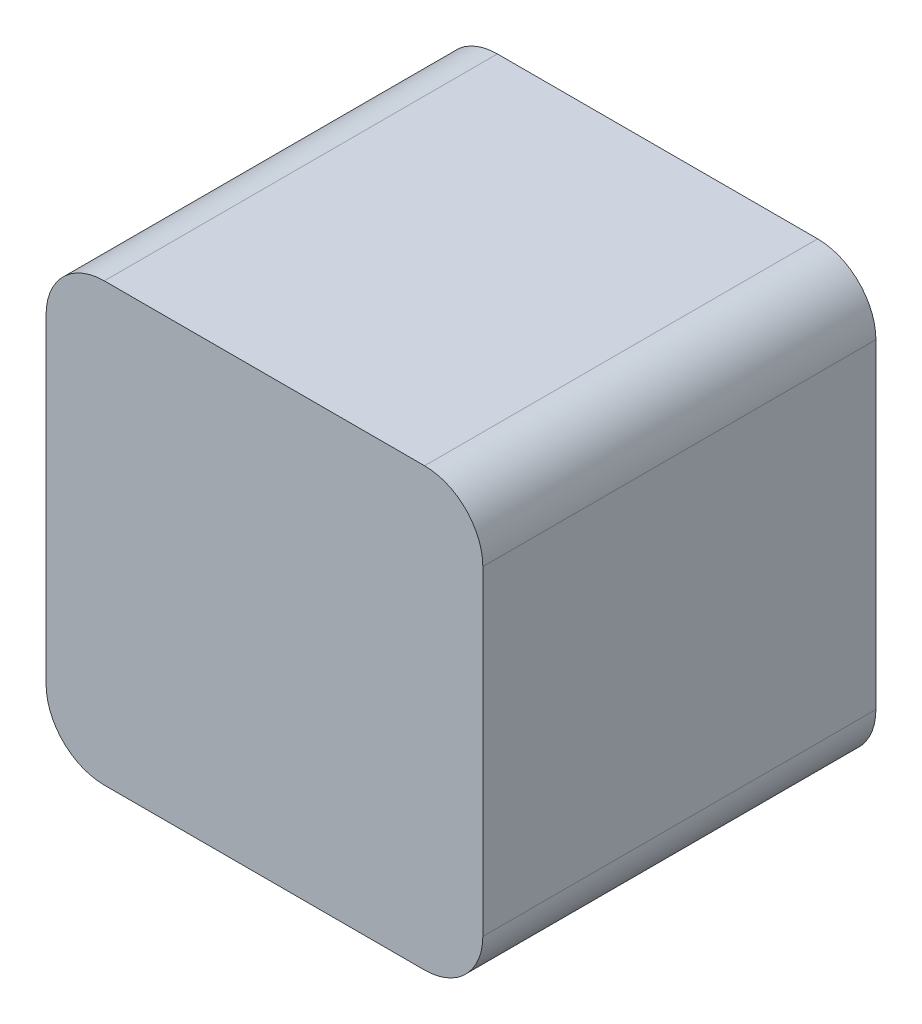
SolidWorks part; units mm, degrees
ref_plane "Front Plane" through (0, 0, 0) normal (0, 0, 1) x (1, 0, 0)
ref_plane "Top Plane" through (0, 0, 0) normal (0, 1, 0) x (1, 0, 0)
ref_plane "Right Plane" through (0, 0, 0) normal (1, 0, 0) x (0, 0, -1)
sketch "Sketch1" plane through (0, 0, 0) normal (0, 0, 1) x (1, 0, 0)
  line L0 (1.833, 2.5) -> (-1.833, 2.5) construction
  line L5 (-7.5, -7.5) -> (7.5, -7.5)
  line L6 (-7.5, -7.5) -> (-7.5, 7.5)
  line L7 (-7.5, 7.5) -> (7.5, 7.5)
  line L8 (7.5, -7.5) -> (7.5, 7.5)
  line L9 (-7.5, -7.5) -> (7.5, 7.5) construction
  line L10 (-7.5, 7.5) -> (7.5, -7.5) construction
  line L11 (1.833, 2.5) -> (-1.833, 2.5) construction
  line L12 (-1.6583, 2.5) -> (1.6583, 2.5)
  arc A0 (-1.833, 2.5) -> (1.833, 2.5) centre (0, 0) ccw construction
  arc A1 (-1.833, 2.5) -> (1.833, 2.5) centre (0, 0) ccw construction
  arc A2 (-1.6583, 2.5) -> (1.6583, 2.5) centre (0, 0) ccw
  point P0 (0, 0)
  dimension "D2" = 3
  dimension "D1" = 5
  dimension "D3" = 2.5
extrude "Boss-Extrude1" add sketch "Sketch1" against normal blind 11
fillet "Fillet1" radius 2 4 edges at (7.5, 7.5, -5.5) (7.5, -7.5, -5.5) (-7.5, 7.5, -5.5) (-7.5, -7.5, -5.5)
sketch "Sketch2" plane through (0, 0, 0) normal (0, 0, 1) x (1, 0, 0)
  line L4 (7.5, -5.5) -> (7.5, 5.5)
  line L5 (5.5, 7.5) -> (-5.5, 7.5)
  line L6 (-7.5, 5.5) -> (-7.5, -5.5)
  line L7 (-5.5, -7.5) -> (5.5, -7.5)
  line L8 (7.5, -5.5) -> (7.5, 5.5)
  line L9 (5.5, 7.5) -> (-5.5, 7.5)
  line L10 (-7.5, 5.5) -> (-7.5, -5.5)
  line L11 (-5.5, -7.5) -> (5.5, -7.5)
  arc A4 (7.5, 5.5) -> (5.5, 7.5) centre (5.5, 5.5) ccw
  arc A5 (-5.5, 7.5) -> (-7.5, 5.5) centre (-5.5, 5.5) ccw
  arc A6 (-7.5, -5.5) -> (-5.5, -7.5) centre (-5.5, -5.5) ccw
  arc A7 (5.5, -7.5) -> (7.5, -5.5) centre (5.5, -5.5) ccw
  arc A8 (7.5, 5.5) -> (5.5, 7.5) centre (5.5, 5.5) ccw
  arc A9 (-5.5, 7.5) -> (-7.5, 5.5) centre (-5.5, 5.5) ccw
  arc A10 (-7.5, -5.5) -> (-5.5, -7.5) centre (-5.5, -5.5) ccw
  arc A11 (5.5, -7.5) -> (7.5, -5.5) centre (5.5, -5.5) ccw
  dimension "D1" = 0
extrude "Boss-Extrude2" add sketch "Sketch2" along normal blind 2.5
